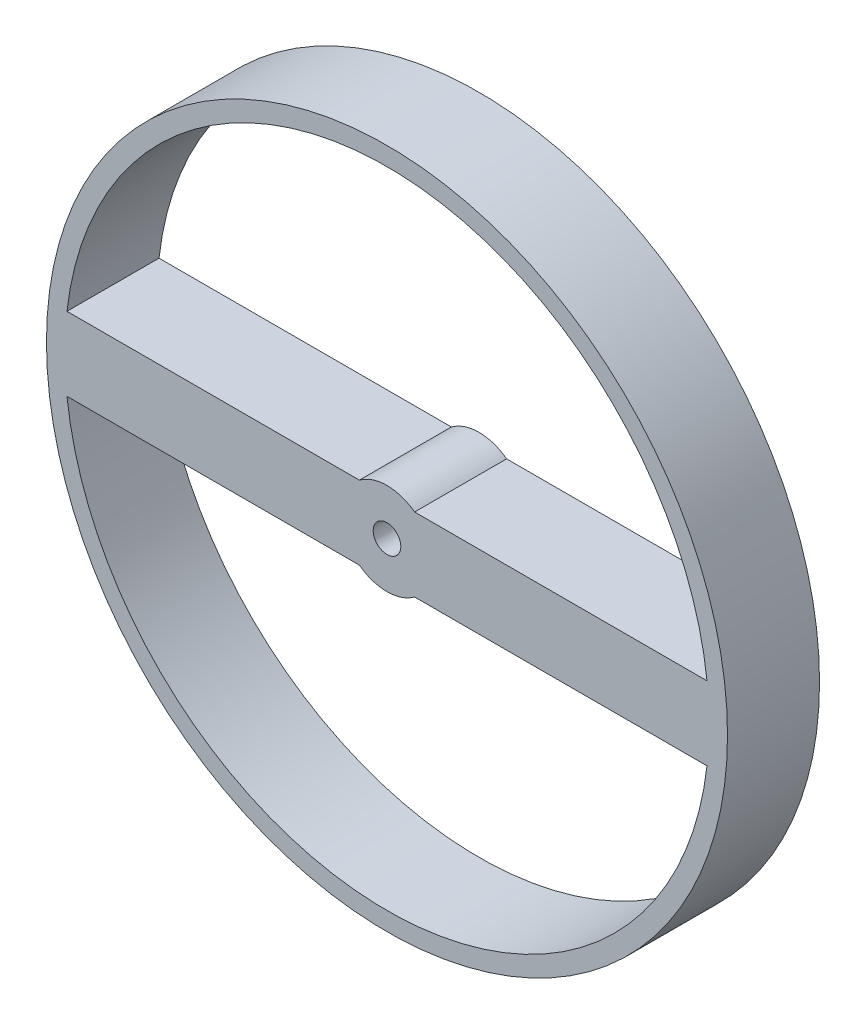
SolidWorks part; units mm, degrees
ref_plane "Alzado" through (0, 0, 0) normal (0, 0, 1) x (1, 0, 0)
ref_plane "Planta" through (0, 0, 0) normal (0, 1, 0) x (1, 0, 0)
ref_plane "Vista lateral" through (0, 0, 0) normal (1, 0, 0) x (0, 0, -1)
sketch "Croquis1" plane through (0, 0, 0) normal (0, 0, 1) x (1, 0, 0)
  circle A0 centre (-21.3223, 7.9588) radius 18.5
  circle A1 centre (-21.3223, 7.9588) radius 0.75
  dimension "D1" = 37
  dimension "D2" = 1.5
extrude "Saliente-Extruir1" add sketch "Croquis1" along normal blind 5 contours A0
sketch "Croquis2" plane through (0, 0, 0) normal (0, 0, -1) x (-1, 0, 0)
  line L0 (20.7653, 26.4504) -> (21.3223, 7.9588) construction
  circle A0 centre (21.3223, 7.9588) radius 18.5 construction
  circle A1 centre (21.3223, 7.9588) radius 0.75
  dimension "D1" = 1.5
extrude "Cortar-Extruir1" cut sketch "Croquis2" against normal blind 5
sketch "Croquis3" plane through (0, 0, 5) normal (0, 0, 1) x (1, 0, 0)
  line L0 (-21.3223, 25.4588) -> (-21.3223, 10.4588) construction
  line L2 (-21.3223, 5.4588) -> (-21.3223, -9.5412) construction
  line L3 (-18.8223, 7.9588) -> (-3.8223, 7.9588) construction
  line L4 (-34.2402, 7.9588) -> (-34.2402, 9.9588) construction
  line L5 (-34.2402, 7.9588) -> (-34.2402, 5.9588) construction
  line L6 (-21.3223, 1.941) -> (-23.3223, 1.941) construction
  line L7 (-21.3223, 1.941) -> (-19.3223, 1.941) construction
  line L8 (-23.3223, 1.941) -> (-23.3223, -9.4265) construction
  line L9 (-19.3223, 1.941) -> (-19.3223, -9.4265) construction
  line L10 (-38.7076, 9.9588) -> (-23.3223, 9.9588) construction
  line L11 (-23.3223, 9.9588) -> (-23.3223, 25.3442) construction
  line L12 (-34.2402, 9.9588) -> (-38.7076, 9.9588) construction
  line L13 (-23.3223, 1.941) -> (-23.3223, 5.9588) construction
  line L15 (-38.7076, 5.9588) -> (-23.3223, 5.9588) construction
  line L16 (-19.3223, 1.941) -> (-19.3223, 5.9588) construction
  line L17 (-19.3223, 5.9588) -> (-3.937, 5.9588) construction
  line L18 (-19.3223, 9.9588) -> (-19.3223, 25.3442) construction
  line L19 (-19.3223, 25.3442) -> (-19.3223, 9.9588) construction
  line L20 (-19.3223, 9.9588) -> (-3.937, 9.9588) construction
  circle A1 centre (-21.3223, 7.9588) radius 17.5
  circle A2 centre (-21.3223, 7.9588) radius 2.5
  dimension "D1" = 35
  dimension "D2" = 5
  dimension "D5" = 2
  dimension "D6" = 2
extrude "Cortar-Extruir4" cut sketch "Croquis3" against normal blind 5
sketch "Croquis6" plane through (0, 0, 5) normal (0, 0, 1) x (1, 0, 0)
  line L0 (-21.3223, 25.4588) -> (-21.3223, 7.9588) construction
  line L1 (-21.3223, 7.9588) -> (-38.8223, 7.9588) construction
  line L2 (-38.8223, 7.9588) -> (-2.8223, 7.9588) construction
  line L3 (-2.8223, 7.9588) -> (-21.3223, 7.9588) construction
  line L4 (-21.3223, 7.9588) -> (-21.3223, -10.5412) construction
  line L6 (-39.7139, 5.9588) -> (-22.2868, 5.9588)
  line L7 (-39.7139, 5.9588) -> (-39.7139, 9.9588)
  line L8 (-39.7139, 9.9588) -> (-22.2868, 9.9588)
  line L9 (-36.0457, 9.9588) -> (-38.7076, 9.9588) construction
  line L10 (-38.7076, 9.9588) -> (-23.3223, 9.9588) construction
  line L11 (-23.3223, 9.9588) -> (-23.3223, 25.3442) construction
  line L12 (-33.6769, 5.9588) -> (-38.7076, 5.9588) construction
  line L13 (-38.7076, 5.9588) -> (-23.3223, 5.9588) construction
  line L14 (-23.3223, 5.9588) -> (-23.3223, -9.4265) construction
  line L15 (-19.3223, 13.4027) -> (-19.3223, 25.3442) construction
  line L16 (-19.3223, 25.3442) -> (-19.3223, 9.9588) construction
  line L17 (-19.3223, 9.9588) -> (-3.937, 9.9588) construction
  line L18 (-19.3223, 5.9588) -> (-19.3223, -9.4265) construction
  line L19 (-19.3223, -9.4265) -> (-19.3223, 5.9588) construction
  line L20 (-19.3223, 5.9588) -> (-3.937, 5.9588) construction
  line L21 (-22.2868, 5.9588) -> (-22.2868, 9.9588)
  line L22 (-23.3223, 26.3504) -> (-19.3223, 26.3504)
  line L23 (-23.3223, 26.3504) -> (-23.3223, 9.4588)
  line L24 (-23.3223, 9.4588) -> (-19.3223, 9.4588)
  line L25 (-19.3223, 26.3504) -> (-19.3223, 9.4588)
  line L26 (-2.9307, 9.9588) -> (-20.0761, 9.9588)
  line L27 (-2.9307, 9.9588) -> (-2.9307, 5.7916)
  line L28 (-2.9307, 5.7916) -> (-20.0761, 5.7916)
  line L29 (-20.0761, 9.9588) -> (-20.0761, 5.7916)
  line L30 (-23.3223, -10.4327) -> (-19.3223, -10.4327)
  line L31 (-23.3223, -10.4327) -> (-23.3223, 6.8371)
  line L32 (-23.3223, 6.8371) -> (-19.3223, 6.8371)
  line L33 (-19.3223, -10.4327) -> (-19.3223, 6.8371)
  circle A0 centre (-21.3223, 7.9588) radius 17.5 construction
  circle A1 centre (-21.3223, 7.9588) radius 18.5 construction
  circle A2 centre (-21.3223, 7.9588) radius 2.5 construction
  spline S0 degree 3 poles (-38.7076, 9.9588) (-38.784, 9.2949) (-38.8606, 7.959) (-38.784, 6.6225) (-38.7076, 5.9588) knots 0 0 0 0 0.499995 1 1 1 1
  spline S1 degree 3 poles (-23.3223, 25.3442) (-22.6585, 25.4206) (-21.3224, 25.4971) (-19.986, 25.4205) (-19.3223, 25.3442) knots 0 0 0 0 0.500001 1 1 1 1
  spline S2 degree 3 poles (-3.937, 9.9588) (-3.8606, 9.2949) (-3.784, 7.959) (-3.8606, 6.6225) (-3.937, 5.9588) knots 0 0 0 0 0.499995 1 1 1 1
  spline S3 degree 3 poles (-19.3223, -9.4265) (-19.986, -9.5029) (-21.3224, -9.5795) (-22.6585, -9.5029) (-23.3223, -9.4265) knots 0 0 0 0 0.499999 1 1 1 1
extrude "Saliente-Extruir11" add sketch "Croquis6" along normal blind 5 from surface at -5 contours L7 L6 L21 L8 starting at face at (-3.8223, 7.9588, 0)
sketch "Croquis8" plane through (0, 0, 5) normal (0, 0, 1) x (1, 0, 0)
  line L0 (-25.4478, 9.9588) -> (-2.9307, 9.9588) construction
  line L1 (-38.7076, 9.9588) -> (-22.8223, 9.9588) construction
  line L3 (-2.9307, 9.9588) -> (-20.1919, 9.9588)
  line L4 (-2.9307, 9.9588) -> (-2.9307, 5.9588)
  line L5 (-2.9307, 5.9588) -> (-20.1919, 5.9588)
  line L6 (-20.1919, 9.9588) -> (-20.1919, 5.9588)
  circle A0 centre (-21.3223, 7.9588) radius 18.5 construction
extrude "Saliente-Extruir12" add sketch "Croquis8" against normal blind 5
